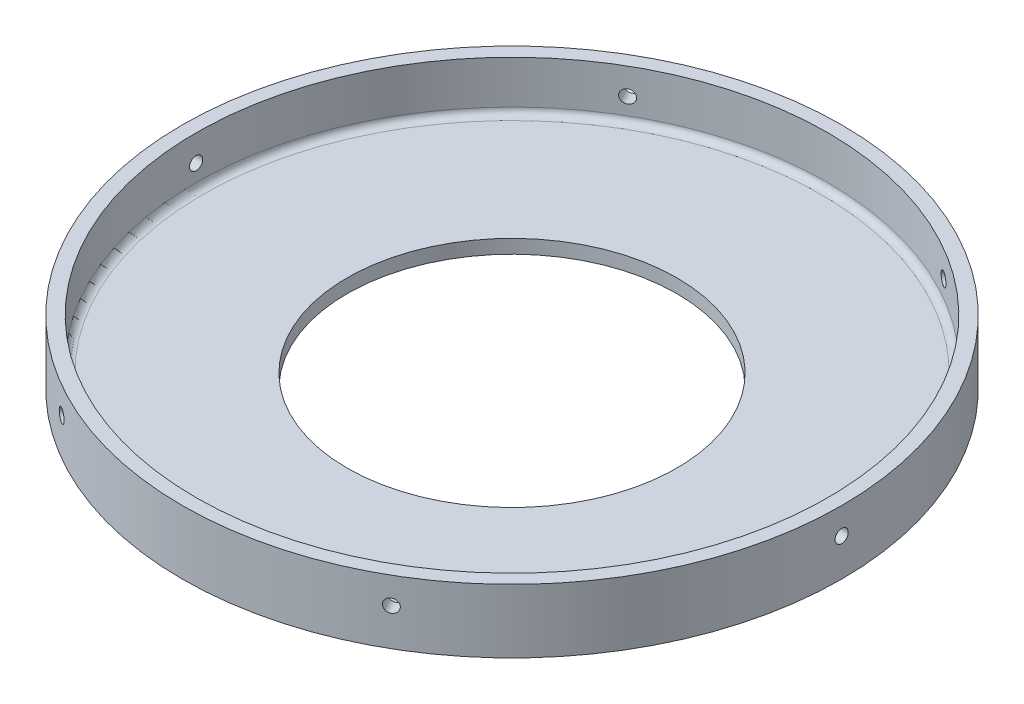
SolidWorks part; units mm, degrees
ref_plane "Front Plane" through (0, 0, 0) normal (0, 0, 1) x (1, 0, 0)
ref_plane "Top Plane" through (0, 0, 0) normal (0, 1, 0) x (1, 0, 0)
ref_plane "Right Plane" through (0, 0, 0) normal (1, 0, 0) x (0, 0, -1)
sketch "Sketch1" plane through (0, 0, 0) normal (0, 1, 0) x (1, 0, 0)
  circle A0 centre (0, 0) radius 76.2
extrude "Boss-Extrude1" add sketch "Sketch1" along normal blind 16.256
shell "Shell1" thickness 3.175
fillet "Fillet1" radius 1.5875 1 edges at (0, 3.175, 73.025)
sketch "Sketch2" plane through (0, 0, 0) normal (0, -1, 0) x (1, 0, 0)
  circle A0 centre (0, 0) radius 38.1
  dimension "D1" = 76.2
extrude "Cut-Extrude1" cut sketch "Sketch2" against normal blind 16.256
sketch "Sketch3" plane through (0, 0, 0) normal (1, 0, 0) x (0, 0, -1)
  line L0 (0, 0) -> (0, 8.636) construction
  circle A0 centre (0, 8.636) radius 1.524
  dimension "D2" = 3.048
  dimension "D1" = 8.636
extrude "Cut-Extrude2" cut sketch "Sketch3" against normal blind 76.2
pattern_circular "CirPattern1" count 6 over 360 about axis through (0, 16.256, 0) along (0, -1, 0) of "Cut-Extrude2"
sketch "Sketch5" plane through (0, 16.256, 0) normal (0, 1, 0) x (1, 0, 0)
  circle A0 centre (0, 0) radius 76.2
extrude "Cut-Extrude4" cut sketch "Sketch5" against normal blind 1.524
